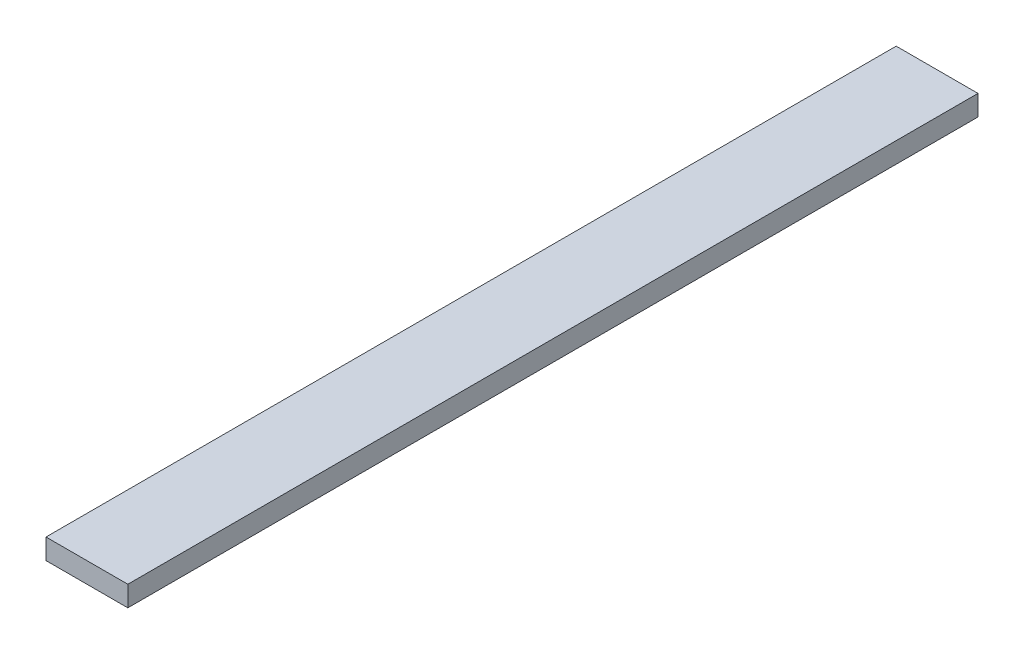
SolidWorks part; units mm, degrees
material "Low Carbon Steel"
ref_plane "Front Plane" through (0, 0, 0) normal (0, 0, 1) x (1, 0, 0)
ref_plane "Top Plane" through (0, 0, 0) normal (0, 1, 0) x (1, 0, 0)
ref_plane "Right Plane" through (0, 0, 0) normal (1, 0, 0) x (0, 0, -1)
sketch "Sketch1" plane through (0, 0, 0) normal (0, 1, 0) x (1, 0, 0)
  line L1 (0, 0) -> (152.4, 0)
  line L2 (0, 0) -> (0, 1583.5)
  line L3 (0, 1583.5) -> (152.4, 1583.5)
  line L4 (152.4, 0) -> (152.4, 1583.5)
  dimension "D1" = 1583.5
  dimension "D2" = 152.4
extrude "Boss-Extrude1" add sketch "Sketch1" along normal blind 38.1
other "Freeze***"
